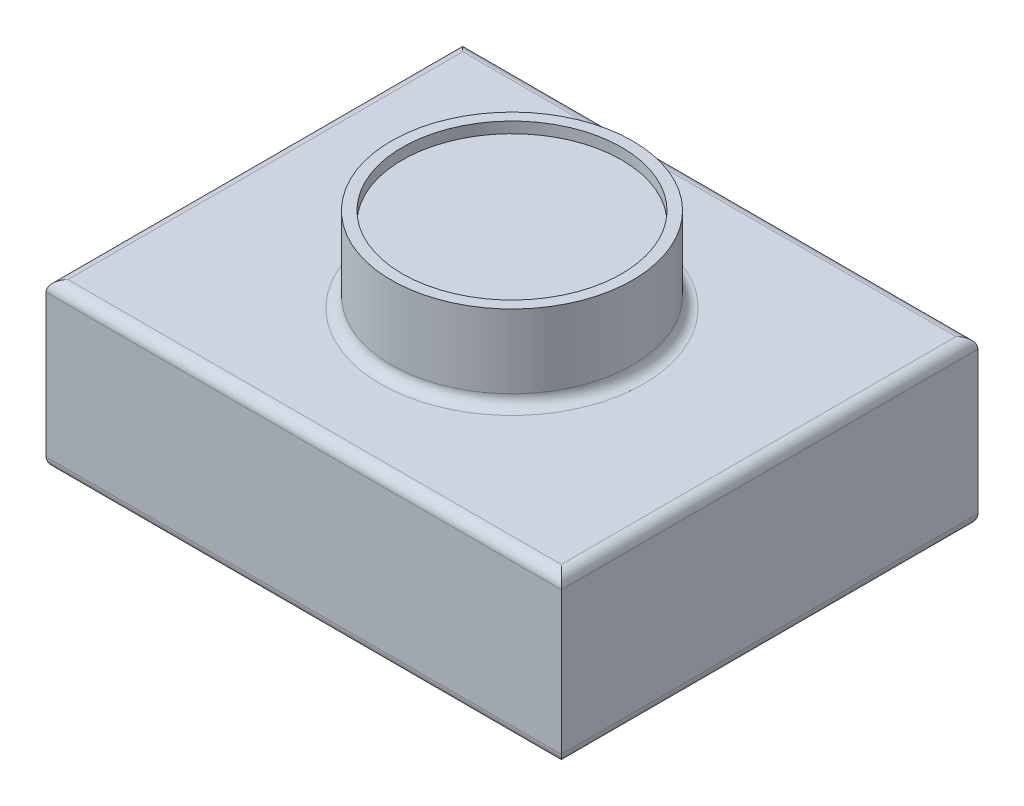
SolidWorks part; units mm, degrees
material "AISI 304"
ref_plane "前视基准面" through (0, 0, 0) normal (0, 0, 1) x (1, 0, 0)
ref_plane "上视基准面" through (0, 0, 0) normal (0, 1, 0) x (1, 0, 0)
ref_plane "右视基准面" through (0, 0, 0) normal (1, 0, 0) x (0, 0, -1)
other "Configuration Table"
sketch "草图1" plane through (0, 0, 0) normal (0, 1, 0) x (1, 0, 0)
  line L1 (-23.5, -19) -> (23.5, -19)
  line L2 (-23.5, -19) -> (-23.5, 19)
  line L3 (-23.5, 19) -> (23.5, 19)
  line L4 (23.5, -19) -> (23.5, 19)
  line L5 (-23.5, -19) -> (23.5, 19) construction
  line L6 (-23.5, 19) -> (23.5, -19) construction
  point P0 (0, 0)
  dimension "D1" = 47
  dimension "D2" = 38
extrude "凸台-拉伸1" add sketch "草图1" along normal blind 15
sketch "草图2" plane through (0, 15, 0) normal (0, 1, 0) x (1, 0, 0)
  circle A0 centre (0, 0) radius 11
  dimension "D1" = 22
extrude "凸台-拉伸2" add sketch "草图2" along normal blind 7.7
fillet "圆角1" radius 1 9 edges at (0, 0, -19) (-23.5, 0, 0) (0, 0, 19) (23.5, 0, 0) (0, 15, 19) (-23.5, 15, 0) (0, 15, -19) (23.5, 15, 0) (0, 15, 11)
sketch "草图3" plane through (0, 0, 0) normal (0, -1, 0) x (1, 0, 0)
  line L0 (0, 0) -> (28.0772, 0) construction
  line L1 (0, 0) -> (0, 27.4829) construction
  line L2 (23.5, 19) -> (23.5, -19) construction
  line L3 (-23.5, -19) -> (-23.5, 19) construction
  line L4 (-23.5, 19) -> (23.5, 19) construction
  line L5 (23.5, -19) -> (-23.5, -19) construction
  line L7 (-11.5, 10) -> (-2.5, 10)
  line L8 (-11.5, 10) -> (-11.5, 16)
  line L9 (-11.5, 16) -> (-2.5, 16)
  line L10 (-2.5, 10) -> (-2.5, 16)
  line L11 (-11.5, 10) -> (-2.5, 16) construction
  line L12 (-11.5, 16) -> (-2.5, 10) construction
  circle A0 centre (19.5, 14) radius 1.5
  circle A1 centre (-19.5, 14) radius 1.5
  circle A2 centre (-19.5, -14) radius 1.5
  circle A3 centre (19.5, -14) radius 1.5
  point P20 (-7, 13)
  dimension "D1" = 3
  dimension "D2" = 3
  dimension "D3" = 3
  dimension "D4" = 3
  dimension "D5" = 4
  dimension "D12" = 5
  dimension "D6" = 4
  dimension "D7" = 4
  dimension "D8" = 4
  dimension "D9" = 5
  dimension "D10" = 5
  dimension "D11" = 5
  dimension "D13" = 9
  dimension "D14" = 6
  dimension "D15" = 3
  dimension "D16" = 12
extrude "切除-拉伸1" cut sketch "草图3" against normal blind 5
sketch "草图4" plane through (0, 5, 0) normal (0, -1, 0) x (1, 0, 0)
  line L0 (-23.5, -19) -> (-23.5, 19) construction
  line L1 (-10, 11) -> (-4, 11)
  line L2 (-10, 11) -> (-10, 15)
  line L3 (-10, 15) -> (-4, 15)
  line L4 (-4, 11) -> (-4, 15)
  line L5 (-10, 11) -> (-4, 15) construction
  line L6 (-10, 15) -> (-4, 11) construction
  line L7 (-23.5, 19) -> (23.5, 19) construction
  point P0 (-7, 13)
  dimension "D1" = 6
  dimension "D2" = 4
  dimension "D3" = 16.5
  dimension "D4" = 6
extrude "凸台-拉伸3" add sketch "草图4" along normal blind 5
sketch "草图5" plane through (0, 22.7, 0) normal (0, 1, 0) x (1, 0, 0)
  circle A0 centre (0, 0) radius 10
  dimension "D1" = 20
extrude "切除-拉伸2" cut sketch "草图5" against normal blind 1
